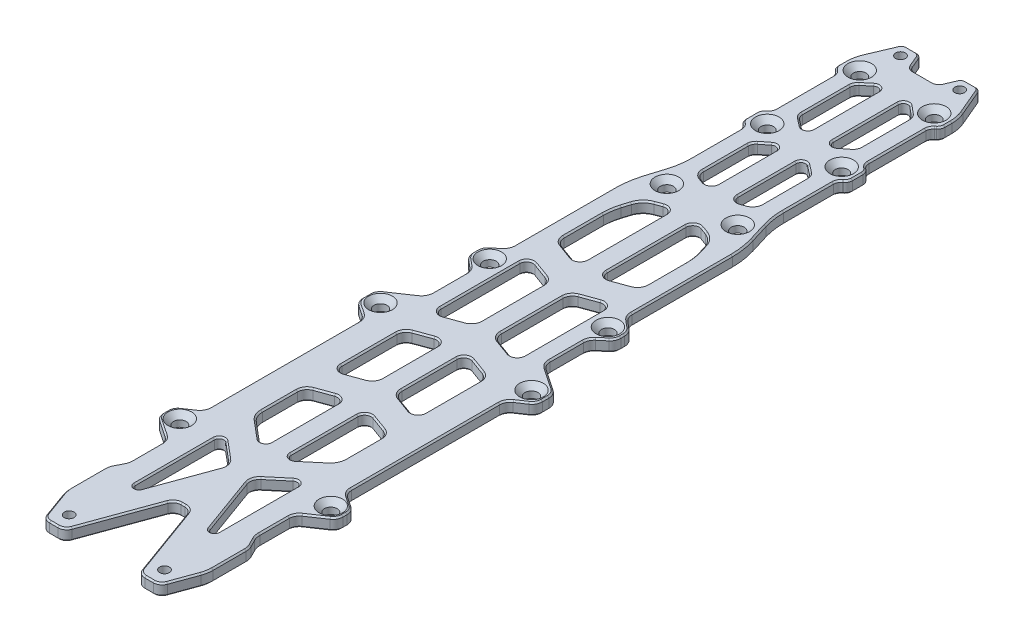
SolidWorks part; units mm, degrees
ref_plane "前视基准面" through (0, 0, 0) normal (0, 0, 1) x (1, 0, 0)
ref_plane "上视基准面" through (0, 0, 0) normal (0, 1, 0) x (1, 0, 0)
ref_plane "右视基准面" through (0, 0, 0) normal (1, 0, 0) x (0, 0, -1)
sketch "草图1" plane through (0, 0, 0) normal (0, 1, 0) x (1, 0, 0)
  line L0 (0, 200322.4044) -> (0, -200266.7138) construction
  line L5 (-3.2357, 178.163) -> (3.2357, 178.163) construction
  line L6 (-6.5891, 182.9444) -> (-5.0767, 179.3815) construction
  line L7 (-11.5825, 184.163) -> (-8.4301, 184.163) construction
  line L8 (-17.0461, 174.4103) -> (-13.4235, 182.9444) construction
  line L9 (-18, 167.3754) -> (-18, 169.7216) construction
  line L10 (-16.7288, 165.0963) -> (-17.0712, 165.3837) construction
  line L11 (-15.8, 143.8248) -> (-15.8, 163.1046) construction
  line L12 (-17.0007, 141.6186) -> (-16.7993, 141.776) construction
  line L13 (-18, 136.106) -> (-18, 139.5698) construction
  line L14 (-16.7993, 133.8998) -> (-17.0007, 134.0572) construction
  line L15 (-15.8, 114.9457) -> (-15.8, 131.851) construction
  line L16 (-22.1516, 90.5838) -> (-16.8487, 107.9288) construction
  line L20 (-28.7631, 23.9743) -> (-27.5869, 24.7676) construction
  line L21 (-30.35, 18.818) -> (-30.35, 20.9897) construction
  line L22 (-27.5869, 15.0402) -> (-28.7631, 15.8335) construction
  line L24 (-25, 48.9901) -> (-20, 44.7946)
  line L25 (-24, -39.422) -> (-24, -30.796) construction
  line L26 (-28.8513, -44.502) -> (-25.4987, -42.2407) construction
  line L27 (-30.35, -48.7051) -> (-30.35, -47.3207) construction
  line L28 (-23.1687, -55.3567) -> (-28.8513, -51.5238) construction
  line L29 (-21.67, -68.1672) -> (-21.67, -58.1754) construction
  line L30 (-23.455, -72.871) -> (-22.215, -70.4372) construction
  line L31 (-24, -86.3272) -> (-24, -75.1409) construction
  line L32 (-20.3508, -98.1165) -> (-23.3969, -89.7474) construction
  line L33 (-14.733, -100.0905) -> (-17.5317, -100.0905) construction
  line L34 (-6.7993, -84.0644) -> (-11.9139, -98.1165) construction
  line L35 (3.9803, -82.0905) -> (-3.9803, -82.0905) construction
  line L36 (0, 200322.4044) -> (0, -200266.7138) construction
  line L37 (-3.2357, 178.163) -> (3.2357, 178.163)
  line L38 (-6.5891, 182.9444) -> (-5.0767, 179.3815)
  line L39 (-11.5825, 184.163) -> (-8.4301, 184.163)
  line L40 (-17.0461, 174.4103) -> (-13.4235, 182.9444)
  line L41 (-18, 167.3754) -> (-18, 169.7216)
  line L42 (-16.7288, 165.0963) -> (-17.0712, 165.3837)
  line L43 (-15.8, 143.8248) -> (-15.8, 163.1046)
  line L44 (-17.0007, 141.6186) -> (-16.7993, 141.776)
  line L45 (-18, 136.106) -> (-18, 139.5698)
  line L46 (-16.7993, 133.8998) -> (-17.0007, 134.0572)
  line L47 (-15.8, 114.9457) -> (-15.8, 131.851)
  line L48 (-20, 97.6213) -> (-16.8487, 107.9288)
  line L52 (-28.7631, 23.9743) -> (-27.5869, 24.7676)
  line L53 (-30.35, 18.818) -> (-30.35, 20.9897)
  line L54 (-27.5869, 15.0402) -> (-28.7631, 15.8335)
  line L56 (-27.5869, 15.0402) -> (-24, 12.6208)
  line L57 (-24, -39.422) -> (-24, -30.796)
  line L58 (-28.8513, -44.502) -> (-25.4987, -42.2407)
  line L59 (-30.35, -48.7051) -> (-30.35, -47.3207)
  line L60 (-23.1687, -55.3567) -> (-28.8513, -51.5238)
  line L61 (-21.67, -68.1672) -> (-21.67, -58.1754)
  line L62 (-23.455, -72.871) -> (-22.215, -70.4372)
  line L63 (-24, -86.3272) -> (-24, -75.1409)
  line L64 (-20.3508, -98.1165) -> (-23.3969, -89.7474)
  line L65 (-14.733, -100.0905) -> (-17.5317, -100.0905)
  line L66 (-6.7993, -84.0644) -> (-11.9139, -98.1165)
  line L67 (3.9803, -82.0905) -> (-3.9803, -82.0905)
  line L68 (20, 44.7946) -> (20, 29.885)
  line L69 (24, 12.6208) -> (24, -30.796)
  line L70 (27.5869, 24.7676) -> (20, 29.885)
  line L71 (25, 53.6532) -> (25, 48.9901)
  line L72 (20, 57.8487) -> (25, 53.6532)
  line L73 (20, 97.6213) -> (20, 57.8487)
  line L74 (6.7993, -84.0644) -> (11.9139, -98.1165)
  line L75 (14.733, -100.0905) -> (17.5317, -100.0905)
  line L76 (20.3508, -98.1165) -> (23.3969, -89.7474)
  line L77 (24, -86.3272) -> (24, -75.1409)
  line L78 (23.455, -72.871) -> (22.215, -70.4372)
  line L79 (21.67, -68.1672) -> (21.67, -58.1754)
  line L80 (23.1687, -55.3567) -> (28.8513, -51.5238)
  line L81 (30.35, -48.7051) -> (30.35, -47.3207)
  line L82 (28.8513, -44.502) -> (25.4987, -42.2407)
  line L83 (24, -39.422) -> (24, -30.796)
  line L84 (27.5869, 15.0402) -> (24, 12.6208)
  line L85 (27.5869, 15.0402) -> (28.7631, 15.8335)
  line L86 (30.35, 18.818) -> (30.35, 20.9897)
  line L87 (28.7631, 23.9743) -> (27.5869, 24.7676)
  line L88 (20, 97.6213) -> (16.8487, 107.9288)
  line L89 (15.8, 114.9457) -> (15.8, 131.851)
  line L90 (16.7993, 133.8998) -> (17.0007, 134.0572)
  line L91 (18, 136.106) -> (18, 139.5698)
  line L92 (17.0007, 141.6186) -> (16.7993, 141.776)
  line L93 (15.8, 143.8248) -> (15.8, 163.1046)
  line L94 (16.7288, 165.0963) -> (17.0712, 165.3837)
  line L95 (18, 167.3754) -> (18, 169.7216)
  line L96 (17.0461, 174.4103) -> (13.4235, 182.9444)
  line L97 (-20, 97.6213) -> (-20, 57.8487)
  line L98 (-20, 57.8487) -> (-25, 53.6532)
  line L99 (-25, 53.6532) -> (-25, 48.9901)
  line L100 (-27.5869, 24.7676) -> (-20, 29.885)
  line L101 (-24, 12.6208) -> (-24, -30.796)
  line L102 (-20, 44.7946) -> (-20, 29.885)
  line L103 (-26, 27.7521) -> (-26, 60.5081) construction
  line L104 (11.5825, 184.163) -> (8.4301, 184.163)
  line L105 (6.5891, 182.9444) -> (5.0767, 179.3815)
  line L106 (25, 48.9901) -> (20, 44.7946)
  arc A0 (-5.0767, 179.3815) -> (-3.2357, 178.163) centre (-3.2357, 180.163) ccw construction
  arc A1 (-6.5891, 182.9444) -> (-8.4301, 184.163) centre (-8.4301, 182.163) ccw construction
  arc A2 (-11.5825, 184.163) -> (-13.4235, 182.9444) centre (-11.5825, 182.163) ccw construction
  arc A3 (-17.0461, 174.4103) -> (-18, 169.7216) centre (-6, 169.7216) ccw construction
  arc A4 (-18, 167.3754) -> (-17.0712, 165.3837) centre (-15.4, 167.3754) ccw construction
  arc A5 (-15.8, 163.1046) -> (-16.7288, 165.0963) centre (-18.4, 163.1046) ccw construction
  arc A6 (-16.7993, 141.776) -> (-15.8, 143.8248) centre (-18.4, 143.8248) ccw construction
  arc A7 (-17.0007, 141.6186) -> (-18, 139.5698) centre (-15.4, 139.5698) ccw construction
  arc A8 (-18, 136.106) -> (-17.0007, 134.0572) centre (-15.4, 136.106) ccw construction
  arc A9 (-15.8, 131.851) -> (-16.7993, 133.8998) centre (-18.4, 131.851) ccw construction
  arc A10 (-16.8487, 107.9288) -> (-15.8, 114.9457) centre (-39.8, 114.9457) ccw construction
  arc A17 (-28.7631, 23.9743) -> (-30.35, 20.9897) centre (-26.75, 20.9897) ccw construction
  arc A18 (-30.35, 18.818) -> (-28.7631, 15.8335) centre (-26.75, 18.818) ccw construction
  arc A25 (-25.4987, -42.2407) -> (-24, -39.422) centre (-27.4, -39.422) ccw construction
  arc A26 (-28.8513, -44.502) -> (-30.35, -47.3207) centre (-26.95, -47.3207) ccw construction
  arc A27 (-30.35, -48.7051) -> (-28.8513, -51.5238) centre (-26.95, -48.7051) ccw construction
  arc A28 (-21.67, -58.1754) -> (-23.1687, -55.3567) centre (-25.07, -58.1754) ccw construction
  arc A29 (-22.215, -70.4372) -> (-21.67, -68.1672) centre (-26.67, -68.1672) ccw construction
  arc A30 (-23.455, -72.871) -> (-24, -75.1409) centre (-19, -75.1409) ccw construction
  arc A31 (-24, -86.3272) -> (-23.3969, -89.7474) centre (-14, -86.3272) ccw construction
  arc A32 (-20.3508, -98.1165) -> (-17.5317, -100.0905) centre (-17.5317, -97.0905) ccw construction
  arc A33 (-14.733, -100.0905) -> (-11.9139, -98.1165) centre (-14.733, -97.0905) ccw construction
  arc A34 (-3.9803, -82.0905) -> (-6.7993, -84.0644) centre (-3.9803, -85.0905) ccw construction
  arc A35 (-5.0767, 179.3815) -> (-3.2357, 178.163) centre (-3.2357, 180.163) ccw
  arc A36 (-6.5891, 182.9444) -> (-8.4301, 184.163) centre (-8.4301, 182.163) ccw
  arc A37 (-11.5825, 184.163) -> (-13.4235, 182.9444) centre (-11.5825, 182.163) ccw
  arc A38 (-17.0461, 174.4103) -> (-18, 169.7216) centre (-6, 169.7216) ccw
  arc A39 (-18, 167.3754) -> (-17.0712, 165.3837) centre (-15.4, 167.3754) ccw
  arc A40 (-15.8, 163.1046) -> (-16.7288, 165.0963) centre (-18.4, 163.1046) ccw
  arc A41 (-16.7993, 141.776) -> (-15.8, 143.8248) centre (-18.4, 143.8248) ccw
  arc A42 (-17.0007, 141.6186) -> (-18, 139.5698) centre (-15.4, 139.5698) ccw
  arc A43 (-18, 136.106) -> (-17.0007, 134.0572) centre (-15.4, 136.106) ccw
  arc A44 (-15.8, 131.851) -> (-16.7993, 133.8998) centre (-18.4, 131.851) ccw
  arc A45 (-16.8487, 107.9288) -> (-15.8, 114.9457) centre (-39.8, 114.9457) ccw
  arc A46 (3.9803, -82.0905) -> (6.7993, -84.0644) centre (3.9803, -85.0905) cw
  arc A47 (14.733, -100.0905) -> (11.9139, -98.1165) centre (14.733, -97.0905) cw
  arc A48 (20.3508, -98.1165) -> (17.5317, -100.0905) centre (17.5317, -97.0905) cw
  arc A49 (24, -86.3272) -> (23.3969, -89.7474) centre (14, -86.3272) cw
  arc A51 (23.455, -72.871) -> (24, -75.1409) centre (19, -75.1409) cw
  arc A52 (-28.7631, 23.9743) -> (-30.35, 20.9897) centre (-26.75, 20.9897) ccw
  arc A53 (-30.35, 18.818) -> (-28.7631, 15.8335) centre (-26.75, 18.818) ccw
  arc A55 (22.215, -70.4372) -> (21.67, -68.1672) centre (26.67, -68.1672) cw
  arc A56 (21.67, -58.1754) -> (23.1687, -55.3567) centre (25.07, -58.1754) cw
  arc A58 (30.35, -48.7051) -> (28.8513, -51.5238) centre (26.95, -48.7051) cw
  arc A59 (28.8513, -44.502) -> (30.35, -47.3207) centre (26.95, -47.3207) cw
  arc A60 (-25.4987, -42.2407) -> (-24, -39.422) centre (-27.4, -39.422) ccw
  arc A61 (-28.8513, -44.502) -> (-30.35, -47.3207) centre (-26.95, -47.3207) ccw
  arc A62 (-30.35, -48.7051) -> (-28.8513, -51.5238) centre (-26.95, -48.7051) ccw
  arc A63 (-21.67, -58.1754) -> (-23.1687, -55.3567) centre (-25.07, -58.1754) ccw
  arc A64 (-22.215, -70.4372) -> (-21.67, -68.1672) centre (-26.67, -68.1672) ccw
  arc A65 (-23.455, -72.871) -> (-24, -75.1409) centre (-19, -75.1409) ccw
  arc A66 (-24, -86.3272) -> (-23.3969, -89.7474) centre (-14, -86.3272) ccw
  arc A67 (-20.3508, -98.1165) -> (-17.5317, -100.0905) centre (-17.5317, -97.0905) ccw
  arc A68 (-14.733, -100.0905) -> (-11.9139, -98.1165) centre (-14.733, -97.0905) ccw
  arc A69 (-3.9803, -82.0905) -> (-6.7993, -84.0644) centre (-3.9803, -85.0905) ccw
  arc A70 (25.4987, -42.2407) -> (24, -39.422) centre (27.4, -39.422) cw
  arc A71 (30.35, 18.818) -> (28.7631, 15.8335) centre (26.75, 18.818) cw
  arc A72 (28.7631, 23.9743) -> (30.35, 20.9897) centre (26.75, 20.9897) cw
  arc A73 (16.8487, 107.9288) -> (15.8, 114.9457) centre (39.8, 114.9457) cw
  arc A74 (15.8, 131.851) -> (16.7993, 133.8998) centre (18.4, 131.851) cw
  arc A75 (18, 136.106) -> (17.0007, 134.0572) centre (15.4, 136.106) cw
  arc A76 (17.0007, 141.6186) -> (18, 139.5698) centre (15.4, 139.5698) cw
  arc A77 (16.7993, 141.776) -> (15.8, 143.8248) centre (18.4, 143.8248) cw
  arc A78 (15.8, 163.1046) -> (16.7288, 165.0963) centre (18.4, 163.1046) cw
  arc A79 (18, 167.3754) -> (17.0712, 165.3837) centre (15.4, 167.3754) cw
  arc A80 (17.0461, 174.4103) -> (18, 169.7216) centre (6, 169.7216) cw
  arc A81 (11.5825, 184.163) -> (13.4235, 182.9444) centre (11.5825, 182.163) cw
  arc A82 (6.5891, 182.9444) -> (8.4301, 184.163) centre (8.4301, 182.163) cw
  arc A83 (5.0767, 179.3815) -> (3.2357, 178.163) centre (3.2357, 180.163) cw
  circle A85 centre (16.1324, -94.8905) radius 1.65
  circle A86 centre (16.1324, -94.8905) radius 1.65
  circle A87 centre (-16.1324, -94.8905) radius 1.65
  circle A88 centre (-16.1324, -94.8905) radius 1.65
  circle A89 centre (25.55, -48.0129) radius 2.15
  circle A90 centre (25.55, -48.0129) radius 2.15
  circle A91 centre (-25.55, -48.0129) radius 2.15
  circle A92 centre (-25.55, -48.0129) radius 2.15
  circle A93 centre (-25.55, 19.9039) radius 2.2
  circle A94 centre (-25.55, 19.9039) radius 2.2
  circle A95 centre (25.55, 19.9039) radius 2.2
  circle A96 centre (25.55, 19.9039) radius 2.2
  circle A97 centre (-20, 51.3216) radius 2.2
  circle A98 centre (-20, 51.3216) radius 2.2
  circle A99 centre (20, 51.3216) radius 2.2
  circle A100 centre (20, 51.3216) radius 2.2
  circle A101 centre (12, 103.2663) radius 2.2
  circle A102 centre (12, 103.2663) radius 2.2
  circle A103 centre (-12, 103.2663) radius 2.2
  circle A104 centre (-12, 103.2663) radius 2.2
  circle A105 centre (12.6, 137.8379) radius 2.15
  circle A106 centre (12.6, 137.8379) radius 2.15
  circle A107 centre (-12.6, 137.8379) radius 2.15
  circle A108 centre (-12.6, 137.8379) radius 2.15
  circle A109 centre (-12.6, 169.163) radius 2.15
  circle A110 centre (-12.6, 169.163) radius 2.15
  circle A111 centre (12.6, 169.163) radius 2.15
  circle A112 centre (12.6, 169.163) radius 2.15
  circle A113 centre (10.0063, 180.363) radius 1.65
  circle A114 centre (10.0063, 180.363) radius 1.65
  circle A115 centre (-10.0063, 180.363) radius 1.65
  circle A116 centre (-10.0063, 180.363) radius 1.65
  point P145 (20, 51.3216)
  point P146 (12, 103.2663)
  point P206 (-12, 103.2663)
  point P211 (-20, 51.3216)
  dimension "D1" = 8
  dimension "D2" = 5
  dimension "D3" = 5
  dimension "D4" = 5
  dimension "D5" = 130
  dimension "D6" = 130
  dimension "D7" = 6
  dimension "D8" = 0
  dimension "D9" = 0
  dimension "D10" = 0
  dimension "D11" = 0
  dimension "D12" = 0
  dimension "D13" = 0
  dimension "D14" = 0
  dimension "D15" = 0
  dimension "D16" = 0
  dimension "D17" = 0
  dimension "D18" = 0
  dimension "D19" = 0
  dimension "D20" = 0
  dimension "D21" = 0
  dimension "D22" = 0
  dimension "D23" = 0
extrude "凸台-拉伸1" add sketch "草图1" along normal blind 4
sketch "草图2" plane through (0, 4, 0) normal (0, 1, 0) x (1, 0, 0)
  line L0 (-7.8261, 110.6404) -> (-6.184, 110.0428) construction
  line L1 (-9.8, 128.6477) -> (-9.8, 113.4595) construction
  line L2 (-6.0851, 132.8182) -> (-8.8007, 130.6965) construction
  line L3 (-3.5, 111.9221) -> (-3.5, 131.5574) construction
  line L4 (-8.8007, 144.9793) -> (-6.0851, 142.8576) construction
  line L5 (-9.8, 163.1046) -> (-9.8, 147.0281) construction
  line L6 (0, 200322.4044) -> (0, -200266.7138) construction
  line L7 (-6.1285, 167.3977) -> (-8.8712, 165.0963) construction
  line L8 (-3.5, 144.1184) -> (-3.5, 166.1721) construction
  line L9 (-7.8261, 110.6404) -> (-6.184, 110.0428)
  line L10 (-9.8, 128.6477) -> (-9.8, 113.4595)
  line L11 (-6.0851, 132.8182) -> (-8.8007, 130.6965)
  line L12 (-3.5, 111.9221) -> (-3.5, 131.5574)
  line L13 (-8.8007, 144.9793) -> (-6.0851, 142.8576)
  line L14 (-9.8, 163.1046) -> (-9.8, 147.0281)
  line L15 (0, 200322.4044) -> (0, -200266.7138) construction
  line L16 (-6.1285, 167.3977) -> (-8.8712, 165.0963)
  line L17 (-3.5, 144.1184) -> (-3.5, 166.1721)
  line L18 (-3.5, 94.3248) -> (-3.5, 67.6086)
  line L19 (-6.4524, 65.5413) -> (-11.8945, 67.522)
  line L20 (-14, 70.5291) -> (-14, 83.7735)
  line L21 (-8.7185, 95.5673) -> (-6.4524, 96.3921)
  line L22 (-14, 55.5689) -> (-14, 28.8527)
  line L23 (-11.0476, 26.7854) -> (-5.6055, 28.7661)
  line L24 (-3.5, 31.7731) -> (-3.5, 52.6484)
  line L25 (-11.9139, -98.1165) -> (-6.7993, -84.0644) construction
  line L26 (-5.6055, 55.6555) -> (-11.0476, 57.6362)
  line L27 (-14, 13.8925) -> (-14, -4.7249)
  line L28 (-11.0476, -6.7922) -> (-5.6055, -4.8115)
  line L29 (-3.5, -1.8045) -> (-3.5, 16.813)
  line L30 (-6.4524, 18.8803) -> (-11.8945, 16.8995)
  line L31 (-14, -47.8537) -> (-14, -74.6169)
  line L32 (-11.6724, -75.0273) -> (-4.4741, -55.2501)
  line L34 (-5.4538, -51.5935) -> (-11.3715, -46.628)
  line L35 (-12.4042, 91.6834) -> (-13.2135, 89.0362)
  line L36 (-16.8487, 107.9288) -> (-20, 97.6213) construction
  line L37 (-20, 97.6213) -> (-20, 57.8487) construction
  line L38 (-6.184, 110.0428) -> (-0.2567, 107.8854) construction
  line L39 (-3.5, 111.9221) -> (-3.5, 107.5103) construction
  line L40 (-3.5, 109.0658) -> (-3.5, 97.4667) construction
  line L42 (-12.2139, -35.4779) -> (-6.1285, -40.5842)
  line L43 (-3.5, -39.3585) -> (-3.5, -16.7646)
  line L44 (-6.4524, -14.6973) -> (-11.8945, -16.6781)
  line L45 (-14, -19.6851) -> (-14, -31.6476)
  line L46 (14, -19.6851) -> (14, -31.6476)
  line L47 (6.4524, -14.6973) -> (11.8945, -16.6781)
  line L48 (3.5, -39.3585) -> (3.5, -16.7646)
  line L49 (12.2139, -35.4779) -> (6.1285, -40.5842)
  line L50 (12.4042, 91.6834) -> (13.2135, 89.0362)
  line L51 (5.4538, -51.5935) -> (11.3715, -46.628)
  line L52 (11.6724, -75.0273) -> (4.4741, -55.2501)
  line L53 (14, -47.8537) -> (14, -74.6169)
  line L54 (6.4524, 18.8803) -> (11.8945, 16.8995)
  line L55 (3.5, -1.8045) -> (3.5, 16.813)
  line L56 (11.0476, -6.7922) -> (5.6055, -4.8115)
  line L57 (14, 13.8925) -> (14, -4.7249)
  line L58 (5.6055, 55.6555) -> (11.0476, 57.6362)
  line L59 (3.5, 31.7731) -> (3.5, 52.6484)
  line L60 (11.0476, 26.7854) -> (5.6055, 28.7661)
  line L61 (14, 55.5689) -> (14, 28.8527)
  line L62 (8.7185, 95.5673) -> (6.4524, 96.3921)
  line L63 (14, 70.5291) -> (14, 83.7735)
  line L64 (6.4524, 65.5413) -> (11.8945, 67.522)
  line L65 (3.5, 94.3248) -> (3.5, 67.6086)
  line L66 (3.5, 144.1184) -> (3.5, 166.1721)
  line L67 (6.1285, 167.3977) -> (8.8712, 165.0963)
  line L68 (9.8, 163.1046) -> (9.8, 147.0281)
  line L69 (8.8007, 144.9793) -> (6.0851, 142.8576)
  line L70 (3.5, 111.9221) -> (3.5, 131.5574)
  line L71 (6.0851, 132.8182) -> (8.8007, 130.6965)
  line L72 (9.8, 128.6477) -> (9.8, 113.4595)
  line L73 (7.8261, 110.6404) -> (6.184, 110.0428)
  line L74 (-6.7993, -84.0644) -> (-3.2706, -74.3691)
  line L75 (-0.6394, -72.5268) -> (0.6394, -72.5268)
  line L76 (-6.7993, -84.0644) -> (6.7993, -84.0644)
  line L77 (6.7993, -84.0644) -> (3.2706, -74.3691)
  arc A0 (-9.8, 113.4595) -> (-7.8261, 110.6404) centre (-6.8, 113.4595) ccw construction
  arc A1 (-6.184, 110.0428) -> (-3.5, 111.9221) centre (-5.5, 111.9221) ccw construction
  arc A2 (-8.8007, 130.6965) -> (-9.8, 128.6477) centre (-7.2, 128.6477) ccw construction
  arc A3 (-3.5, 131.5574) -> (-6.0851, 132.8182) centre (-5.1, 131.5574) ccw construction
  arc A4 (-9.8, 147.0281) -> (-8.8007, 144.9793) centre (-7.2, 147.0281) ccw construction
  arc A5 (-6.0851, 142.8576) -> (-3.5, 144.1184) centre (-5.1, 144.1184) ccw construction
  arc A6 (-8.8712, 165.0963) -> (-9.8, 163.1046) centre (-7.2, 163.1046) ccw construction
  arc A7 (-3.5, 166.1721) -> (-6.1285, 167.3977) centre (-5.1, 166.1721) ccw construction
  arc A8 (-9.8, 113.4595) -> (-7.8261, 110.6404) centre (-6.8, 113.4595) ccw
  arc A9 (-6.184, 110.0428) -> (-3.5, 111.9221) centre (-5.5, 111.9221) ccw
  arc A10 (-8.8007, 130.6965) -> (-9.8, 128.6477) centre (-7.2, 128.6477) ccw
  arc A11 (-3.5, 131.5574) -> (-6.0851, 132.8182) centre (-5.1, 131.5574) ccw
  arc A12 (-9.8, 147.0281) -> (-8.8007, 144.9793) centre (-7.2, 147.0281) ccw
  arc A13 (-6.0851, 142.8576) -> (-3.5, 144.1184) centre (-5.1, 144.1184) ccw
  arc A14 (-8.8712, 165.0963) -> (-9.8, 163.1046) centre (-7.2, 163.1046) ccw
  arc A15 (-3.5, 166.1721) -> (-6.1285, 167.3977) centre (-5.1, 166.1721) ccw
  arc A16 (3.5, 166.1721) -> (6.1285, 167.3977) centre (5.1, 166.1721) cw
  arc A17 (8.8712, 165.0963) -> (9.8, 163.1046) centre (7.2, 163.1046) cw
  arc A18 (6.0851, 142.8576) -> (3.5, 144.1184) centre (5.1, 144.1184) cw
  arc A19 (9.8, 147.0281) -> (8.8007, 144.9793) centre (7.2, 147.0281) cw
  arc A20 (3.5, 131.5574) -> (6.0851, 132.8182) centre (5.1, 131.5574) cw
  arc A21 (8.8007, 130.6965) -> (9.8, 128.6477) centre (7.2, 128.6477) cw
  arc A22 (6.184, 110.0428) -> (3.5, 111.9221) centre (5.5, 111.9221) cw
  arc A23 (9.8, 113.4595) -> (7.8261, 110.6404) centre (6.8, 113.4595) cw
  arc A24 (6.4524, 96.3921) -> (3.5, 94.3248) centre (5.7, 94.3248) ccw
  arc A25 (-3.5, 94.3248) -> (-6.4524, 96.3921) centre (-5.7, 94.3248) ccw
  arc A26 (-14, 28.8527) -> (-11.0476, 26.7854) centre (-11.8, 28.8527) ccw
  arc A27 (11.0476, 26.7854) -> (14, 28.8527) centre (11.8, 28.8527) ccw
  arc A28 (6.4524, -14.6973) -> (3.5, -16.7646) centre (5.7, -16.7646) ccw
  arc A29 (-3.5, -16.7646) -> (-6.4524, -14.6973) centre (-5.7, -16.7646) ccw
  arc A30 (11.0476, -6.7922) -> (14, -4.7249) centre (11.8, -4.7249) ccw
  arc A31 (-14, -4.7249) -> (-11.0476, -6.7922) centre (-11.8, -4.7249) ccw
  arc A32 (6.4524, 18.8803) -> (3.5, 16.813) centre (5.7, 16.813) ccw
  arc A33 (-3.5, 16.813) -> (-6.4524, 18.8803) centre (-5.7, 16.813) ccw
  arc A34 (11.0476, 57.6362) -> (14, 55.5689) centre (11.8, 55.5689) cw
  arc A35 (6.4524, 65.5413) -> (3.5, 67.6086) centre (5.7, 67.6086) cw
  arc A36 (-14, 55.5689) -> (-11.0476, 57.6362) centre (-11.8, 55.5689) cw
  arc A37 (-3.5, 67.6086) -> (-6.4524, 65.5413) centre (-5.7, 67.6086) cw
  arc A38 (14, -19.6851) -> (11.8945, -16.6781) centre (10.8, -19.6851) ccw
  arc A39 (-11.8945, -16.6781) -> (-14, -19.6851) centre (-10.8, -19.6851) ccw
  arc A40 (11.8945, 16.8995) -> (14, 13.8925) centre (10.8, 13.8925) cw
  arc A41 (3.5, -1.8045) -> (5.6055, -4.8115) centre (6.7, -1.8045) ccw
  arc A42 (-5.6055, -4.8115) -> (-3.5, -1.8045) centre (-6.7, -1.8045) ccw
  arc A43 (-14, 13.8925) -> (-11.8945, 16.8995) centre (-10.8, 13.8925) cw
  arc A44 (3.5, 31.7731) -> (5.6055, 28.7661) centre (6.7, 31.7731) ccw
  arc A45 (5.6055, 55.6555) -> (3.5, 52.6484) centre (6.7, 52.6484) ccw
  arc A46 (-3.5, 52.6484) -> (-5.6055, 55.6555) centre (-6.7, 52.6484) ccw
  arc A47 (-5.6055, 28.7661) -> (-3.5, 31.7731) centre (-6.7, 31.7731) ccw
  arc A48 (14, 70.5291) -> (11.8945, 67.522) centre (10.8, 70.5291) cw
  arc A49 (-11.8945, 67.522) -> (-14, 70.5291) centre (-10.8, 70.5291) cw
  arc A50 (13.2135, 89.0362) -> (14, 83.7735) centre (-4, 83.7735) cw
  arc A51 (-13.2135, 89.0362) -> (-14, 83.7735) centre (4, 83.7735) ccw
  arc A52 (12.4042, 91.6834) -> (8.7185, 95.5673) centre (6.6663, 89.9292) ccw
  arc A53 (-12.4042, 91.6834) -> (-8.7185, 95.5673) centre (-6.6663, 89.9292) cw
  arc A54 (3.5, -39.3585) -> (6.1285, -40.5842) centre (5.1, -39.3585) ccw
  arc A55 (-6.1285, -40.5842) -> (-3.5, -39.3585) centre (-5.1, -39.3585) ccw
  arc A56 (14, -31.6476) -> (12.2139, -35.4779) centre (9, -31.6476) cw
  arc A57 (-12.2139, -35.4779) -> (-14, -31.6476) centre (-9, -31.6476) cw
  arc A58 (11.3715, -46.628) -> (14, -47.8537) centre (12.4, -47.8537) cw
  arc A59 (-14, -47.8537) -> (-11.3715, -46.628) centre (-12.4, -47.8537) cw
  arc A60 (5.4538, -51.5935) -> (4.4741, -55.2501) centre (7.575, -54.1215) ccw
  arc A61 (-4.4741, -55.2501) -> (-5.4538, -51.5935) centre (-7.575, -54.1215) ccw
  arc A62 (11.6724, -75.0273) -> (14, -74.6169) centre (12.8, -74.6169) ccw
  arc A63 (-14, -74.6169) -> (-11.6724, -75.0273) centre (-12.8, -74.6169) ccw
  arc A64 (3.2706, -74.3691) -> (0.6394, -72.5268) centre (0.6394, -75.3268) ccw
  arc A65 (-3.2706, -74.3691) -> (-0.6394, -72.5268) centre (-0.6394, -75.3268) cw
  point P51 (-12, 103.2663)
  point P52 (-3.5, 109.0658)
  point P55 (-3.5, 103.2663)
  point P83 (3.5, 109.0658)
  point P84 (12, 103.2663)
  point P111 (0, -84.0644)
  point P112 (0, -72.5268)
  point P114 (3.5, 97.4667)
  point P120 (-14, 25.7108)
  point P123 (14, 25.7108)
  point P126 (3.5, -13.6227)
  point P129 (-3.5, -13.6227)
  point P132 (14, -7.8668)
  point P135 (-14, -7.8668)
  point P138 (3.5, 19.9549)
  point P141 (-3.5, 19.9549)
  point P144 (14, 58.7108)
  point P147 (3.5, 64.4667)
  point P150 (-14, 58.7108)
  point P153 (-3.5, 64.4667)
  point P156 (14, -17.4444)
  point P159 (-14, -17.4444)
  point P162 (14, 16.1332)
  point P165 (3.5, -4.0451)
  point P168 (-3.5, -4.0451)
  point P171 (-14, 16.1332)
  point P174 (3.5, 29.5325)
  point P177 (3.5, 54.8891)
  point P180 (-3.5, 54.8891)
  point P183 (-3.5, 29.5325)
  point P186 (14, 68.2884)
  point P189 (-14, 68.2884)
  point P192 (14, 86.4637)
  point P195 (-14, 86.4637)
  point P198 (11.5295, 94.5442)
  point P201 (-11.5295, 94.5442)
  point P204 (3.5, -42.7897)
  point P207 (-3.5, -42.7897)
  point P210 (14, -33.9792)
  point P213 (-14, -33.9792)
  point P216 (14, -44.4224)
  point P219 (-14, -44.4224)
  point P222 (3.6838, -53.0788)
  point P225 (-3.6838, -53.0788)
  point P228 (14, -81.4224)
  point P231 (-14, -81.4224)
  point P234 (2.6, -72.5268)
  point P237 (-2.6, -72.5268)
  dimension "D17" = 2.2
  dimension "D18" = 3.2
  dimension "D19" = 18
  dimension "D20" = 6
  dimension "D21" = 1.6
  dimension "D22" = 5
  dimension "D23" = 1.6
  dimension "D24" = 3.3
  dimension "D25" = 1.2
  dimension "D26" = 2.8
  dimension "D1" = 6
  dimension "D2" = 9
  dimension "D3" = 70
  dimension "D4" = 33
  dimension "D5" = 110
  dimension "D6" = 9
  dimension "D7" = 9
  dimension "D8" = 33
  dimension "D9" = 110
  dimension "D10" = 7.67
  dimension "D11" = 24
  dimension "D12" = 9
  dimension "D13" = 8
  dimension "D14" = 37
  dimension "D15" = 130
  dimension "D16" = 2.6
extrude "切除-拉伸1" cut sketch "草图2" against normal blind 10
fillet "圆角1" radius 28 2 edges at (20, 2, -97.6213) (-20, 2, -97.6213)
fillet "圆角2" radius 3.6 12 edges at (-24, 2, -12.6208) (24, 2, -12.6208) (20, 2, -57.8487) (25, 2, -53.6532) (25, 2, -48.9901) (20, 2, -44.7946) (20, 2, -29.885) (-20, 2, -57.8487) (-25, 2, -53.6532) (-25, 2, -48.9901) (-20, 2, -44.7946) (-20, 2, -29.885)
chamfer "倒角1" distance 0.5 angle 45 400 edges at (-13.0762, 0, 46.4036) (-14, 0, 61.2353) (-8.4127, 0, 49.1107) (-13.0084, 0, 75.7987) (-4.3875, 0, 53.2674) (-8.0732, 0, 65.1387) (-13.0762, 4, 46.4036) (-14, 4, 61.2353) (-8.4127, 4, 49.1107) (-13.0084, 4, 75.7987) (-4.3875, 4, 53.2674) (-8.0732, 4, 65.1387) (4.3875, 0, 53.2674) (8.0732, 0, 65.1387) (8.4127, 0, 49.1107) (13.0084, 0, 75.7987) (13.0762, 0, 46.4036) (14, 0, 61.2353) (4.3875, 4, 53.2674) (8.0732, 4, 65.1387) (8.4127, 4, 49.1107) (13.0084, 4, 75.7987) (13.0762, 4, 46.4036) (14, 4, 61.2353) (-14, 0, 25.6664) (-13.5315, 0, 33.7607) (-13.4213, 0, 17.8496) (-9.1712, 0, 38.031) (-9.1735, 0, 15.6877) (-4.4238, 0, 40.8086) (-4.4381, 0, 14.9625) (-3.5, 0, 28.0616) (-14, 4, 25.6664) (-13.5315, 4, 33.7607) (-13.4213, 4, 17.8496) (-9.1712, 4, 38.031) (-9.1735, 4, 15.6877) (-4.4238, 4, 40.8086) (-4.4381, 4, 14.9625) (-3.5, 4, 28.0616) (3.5, 0, 28.0616) (4.4238, 0, 40.8086) (4.4381, 0, 14.9625) (9.1712, 0, 38.031) (9.1735, 0, 15.6877) (13.5315, 0, 33.7607) (13.4213, 0, 17.8496) (14, 0, 25.6664) (3.5, 4, 28.0616) (4.4238, 4, 40.8086) (4.4381, 4, 14.9625) (9.1712, 4, 38.031) (9.1735, 4, 15.6877) (13.5315, 4, 33.7607) (13.4213, 4, 17.8496) (14, 4, 25.6664) (3.5, 0, -7.5042) (4.0787, 0, 3.6399) (4.4381, 0, -18.6151) (8.3265, 0, 5.8018) (9.1735, 0, -17.8899) (13.0619, 0, 6.527) (13.4213, 0, -15.728) (14, 0, -4.5838) (3.5, 4, -7.5042) (4.0787, 4, 3.6399) (4.4381, 4, -18.6151) (8.3265, 4, 5.8018) (9.1735, 4, -17.8899) (13.0619, 4, 6.527) (13.4213, 4, -15.728) (14, 4, -4.5838) (-14, 0, -4.5838) (-13.0619, 0, 6.527) (-13.4213, 0, -15.728) (-8.3265, 0, 5.8018) (-9.1735, 0, -17.8899) (-4.0787, 0, 3.6399) (-4.4381, 0, -18.6151) (-3.5, 0, -7.5042) (-14, 4, -4.5838) (-13.0619, 4, 6.527) (-13.4213, 4, -15.728) (-8.3265, 4, 5.8018) (-9.1735, 4, -17.8899) (-4.0787, 4, 3.6399) (-4.4381, 4, -18.6151) (-3.5, 4, -7.5042) (-14, 0, -42.2108) (-13.0619, 0, -27.0506) (-13.0619, 0, -57.371) (-8.3265, 0, -27.7758) (-8.3265, 0, -56.6458) (-4.0787, 0, -29.9377) (-4.0787, 0, -54.4839) (-3.5, 0, -42.2108) (-14, 4, -42.2108) (-13.0619, 4, -27.0506) (-13.0619, 4, -57.371) (-8.3265, 4, -27.7758) (-8.3265, 4, -56.6458) (-4.0787, 4, -29.9377) (-4.0787, 4, -54.4839) (-3.5, 4, -42.2108) (3.5, 0, -42.2108) (4.0787, 0, -29.9377) (4.0787, 0, -54.4839) (8.3265, 0, -27.7758) (8.3265, 0, -56.6458) (13.0619, 0, -27.0506) (13.0619, 0, -57.371) (14, 0, -42.2108) (3.5, 4, -42.2108) (4.0787, 4, -29.9377) (4.0787, 4, -54.4839) (8.3265, 4, -27.7758) (8.3265, 4, -56.6458) (13.0619, 4, -27.0506) (13.0619, 4, -57.371) (14, 4, -42.2108) (-13.8023, 0, -86.4341) (-14, 0, -77.1513) (-12.8088, 0, -90.3598) (-13.4213, 0, -68.6936) (-11.0186, 0, -94.0593) (-9.1735, 0, -66.5317) (-7.5854, 0, -95.9797) (-4.4381, 0, -65.8065) (-4.4381, 0, -96.1269) (-3.5, 0, -80.9667) (-13.8023, 4, -86.4341) (-14, 4, -77.1513) (-12.8088, 4, -90.3598) (-13.4213, 4, -68.6936) (-11.0186, 4, -94.0593) (-9.1735, 4, -66.5317) (-7.5854, 4, -95.9797) (-4.4381, 4, -65.8065) (-4.4381, 4, -96.1269) (-3.5, 4, -80.9667) (4.4381, 0, -96.1269) (3.5, 0, -80.9667) (7.5854, 0, -95.9797) (4.4381, 0, -65.8065) (11.0186, 0, -94.0593) (9.1735, 0, -66.5317) (12.8088, 0, -90.3598) (13.4213, 0, -68.6936) (13.8023, 0, -86.4341) (14, 0, -77.1513) (4.4381, 4, -96.1269) (3.5, 4, -80.9667) (7.5854, 4, -95.9797) (4.4381, 4, -65.8065) (11.0186, 4, -94.0593) (9.1735, 4, -66.5317) (12.8088, 4, -90.3598) (13.4213, 4, -68.6936) (13.8023, 4, -86.4341) (14, 4, -77.1513) (3.5, 0, -121.7398) (4.3528, 0, -110.2838) (4.3986, 0, -132.9955) (7.0051, 0, -110.3416) (7.4429, 0, -131.7574) (9.2575, 0, -111.7387) (9.5369, 0, -129.7875) (9.8, 0, -121.0536) (3.5, 4, -121.7398) (4.3528, 4, -110.2838) (4.3986, 4, -132.9955) (7.0051, 4, -110.3416) (7.4429, 4, -131.7574) (9.2575, 4, -111.7387) (9.5369, 4, -129.7875) (9.8, 4, -121.0536) (-9.8, 0, -121.0536) (-9.2575, 0, -111.7387) (-9.5369, 0, -129.7875) (-7.0051, 0, -110.3416) (-7.4429, 0, -131.7574) (-4.3528, 0, -110.2838) (-4.3986, 0, -132.9955) (-3.5, 0, -121.7398) (-9.8, 4, -121.0536) (-9.2575, 4, -111.7387) (-9.5369, 4, -129.7875) (-7.0051, 4, -110.3416) (-7.4429, 4, -131.7574) (-4.3528, 4, -110.2838) (-4.3986, 4, -132.9955) (-3.5, 4, -121.7398) (-9.8, 0, -155.0663) (-9.5369, 0, -145.8883) (-9.5564, 0, -164.2034) (-7.4429, 0, -143.9184) (-7.4999, 0, -166.247) (-4.3986, 0, -142.6803) (-4.4238, 0, -167.6222) (-3.5, 0, -155.1452) (-9.8, 4, -155.0663) (-9.5369, 4, -145.8883) (-9.5564, 4, -164.2034) (-7.4429, 4, -143.9184) (-7.4999, 4, -166.247) (-4.3986, 4, -142.6803) (-4.4238, 4, -167.6222) (-3.5, 4, -155.1452) (3.5, 0, -155.1452) (4.3986, 0, -142.6803) (4.4238, 0, -167.6222) (7.4429, 0, -143.9184) (7.4999, 0, -166.247) (9.5369, 0, -145.8883) (9.5564, 0, -164.2034) (9.8, 0, -155.0663) (3.5, 4, -155.1452) (4.3986, 4, -142.6803) (4.4238, 4, -167.6222) (7.4429, 4, -143.9184) (7.4999, 4, -166.247) (9.5369, 4, -145.8883) (9.5564, 4, -164.2034) (9.8, 4, -155.0663) (30.35, 0, -19.9039) (29.9286, 0, -22.6798) (29.9286, 0, -17.1279) (25.175, 0, -26.3945) (27.175, 0, -14.7623) (20.4214, 0, -30.1091) (24.4214, 0, -12.3967) (20, 0, -37.4575) (24, 0, 14.3577) (20.3373, 0, -44.6373) (24.398, 0, 41.0182) (22.5, 0, -46.8923) (27.175, 0, 43.3713) (24.6627, 0, -49.1474) (29.952, 0, 45.7245) (25, 0, -51.3216) (30.35, 0, 48.0129) (24.6627, 0, -53.4959) (29.952, 0, 50.3013) (22.5, 0, -55.7509) (26.01, 0, 53.4403) (20.3373, 0, -58.006) (22.068, 0, 56.5792) (20, 0, -76.482) (21.67, 0, 63.1713) (19.6924, 0, -97.5753) (21.8082, 0, 69.3345) (17.8126, 0, -104.7759) (22.835, 0, 71.6541) (16.0636, 0, -111.3983) (23.8618, 0, 73.9737) (15.8, 0, -123.3983) (24, 0, 80.734) (16.0631, 0, -132.9907) (23.8481, 0, 88.0637) (16.9, 0, -133.9785) (21.8739, 0, 93.9319) (17.7369, 0, -134.9662) (19.2525, 0, 99.5479) (18, 0, -137.8379) (16.1324, 0, 100.0905) (17.7369, 0, -140.7096) (13.0123, 0, 99.5479) (16.9, 0, -141.6973) (7.5922, 0, 86.2428) (16.0631, 0, -142.6851) (2.2454, 0, 73.0332) (15.8, 0, -153.4647) (0, 0, 72.5268) (16.0436, 0, -164.2034) (-2.2454, 0, 73.0332) (16.9, 0, -165.24) (-7.5922, 0, 86.2428) (17.7564, 0, -166.2766) (-13.0123, 0, 99.5479) (18, 0, -168.5485) (-16.1324, 0, 100.0905) (17.7591, 0, -172.114) (-19.2525, 0, 99.5479) (15.2348, 0, -178.6774) (-21.8739, 0, 93.9319) (12.6864, 0, -183.8308) (-23.8481, 0, 88.0637) (10.0063, 0, -184.163) (-24, 0, 80.734) (7.3262, 0, -183.8308) (-23.8618, 0, 73.9737) (5.8329, 0, -181.163) (-22.835, 0, 71.6541) (4.3396, 0, -178.4952) (-21.8082, 0, 69.3345) (0, 0, -178.163) (-21.67, 0, 63.1713) (-4.3396, 0, -178.4952) (-22.068, 0, 56.5792) (-5.8329, 0, -181.163) (-26.01, 0, 53.4403) (-7.3262, 0, -183.8308) (-29.952, 0, 50.3013) (-10.0063, 0, -184.163) (-30.35, 0, 48.0129) (-12.6864, 0, -183.8308) (-29.952, 0, 45.7245) (-15.2348, 0, -178.6774) (-27.175, 0, 43.3713) (-17.7591, 0, -172.114) (-24.398, 0, 41.0182) (-18, 0, -168.5485) (-24, 0, 14.3577) (-17.7564, 0, -166.2766) (-24.4214, 0, -12.3967) (-16.9, 0, -165.24) (-27.175, 0, -14.7623) (-16.0436, 0, -164.2034) (-29.9286, 0, -17.1279) (-15.8, 0, -153.4647) (-30.35, 0, -19.9039) (-16.0631, 0, -142.6851) (-29.9286, 0, -22.6798) (-16.9, 0, -141.6973) (-25.175, 0, -26.3945) (-17.7369, 0, -140.7096) (-20.4214, 0, -30.1091) (-18, 0, -137.8379) (-20, 0, -37.4575) (-17.7369, 0, -134.9662) (-20.3373, 0, -44.6373) (-16.9, 0, -133.9785) (-22.5, 0, -46.8923) (-16.0631, 0, -132.9907) (-24.6627, 0, -49.1474) (-15.8, 0, -123.3983) (-25, 0, -51.3216) (-16.0636, 0, -111.3983) (-24.6627, 0, -53.4959) (-17.8126, 0, -104.7759) (-22.5, 0, -55.7509) (-19.6924, 0, -97.5753) (-20.3373, 0, -58.006) (-20, 0, -76.482) (30.35, 4, -19.9039) (29.9286, 4, -22.6798) (29.9286, 4, -17.1279) (25.175, 4, -26.3945) (27.175, 4, -14.7623) (20.4214, 4, -30.1091) (24.4214, 4, -12.3967) (20, 4, -37.4575) (24, 4, 14.3577) (20.3373, 4, -44.6373) (24.398, 4, 41.0182) (22.5, 4, -46.8923) (27.175, 4, 43.3713) (24.6627, 4, -49.1474) (29.952, 4, 45.7245) (25, 4, -51.3216) (30.35, 4, 48.0129) (24.6627, 4, -53.4959) (29.952, 4, 50.3013) (22.5, 4, -55.7509) (26.01, 4, 53.4403) (20.3373, 4, -58.006) (22.068, 4, 56.5792) (20, 4, -76.482) (21.67, 4, 63.1713) (19.6924, 4, -97.5753) (21.8082, 4, 69.3345) (17.8126, 4, -104.7759) (22.835, 4, 71.6541) (16.0636, 4, -111.3983) (23.8618, 4, 73.9737) (15.8, 4, -123.3983) (24, 4, 80.734) (16.0631, 4, -132.9907) (23.8481, 4, 88.0637) (16.9, 4, -133.9785) (21.8739, 4, 93.9319) (17.7369, 4, -134.9662) (19.2525, 4, 99.5479) (18, 4, -137.8379) (16.1324, 4, 100.0905) (17.7369, 4, -140.7096) (13.0123, 4, 99.5479) (16.9, 4, -141.6973) (7.5922, 4, 86.2428) (16.0631, 4, -142.6851) (2.2454, 4, 73.0332) (15.8, 4, -153.4647) (0, 4, 72.5268) (16.0436, 4, -164.2034) (-2.2454, 4, 73.0332) (16.9, 4, -165.24) (-7.5922, 4, 86.2428) (17.7564, 4, -166.2766) (-13.0123, 4, 99.5479) (18, 4, -168.5485)
chamfer "倒角2" distance 1.8 angle 45 6 edges at (25.55, 4, -17.7039) (-25.55, 4, -17.7039) (-20, 4, -49.1216) (20, 4, -49.1216) (-12, 4, -101.0663) (12, 4, -101.0663)
chamfer "倒角3" distance 1.85 angle 45 6 edges at (25.55, 4, 50.1629) (-25.55, 4, 50.1629) (12.6, 4, -167.013) (-12.6, 4, -167.013) (-12.6, 4, -135.6879) (12.6, 4, -135.6879)
